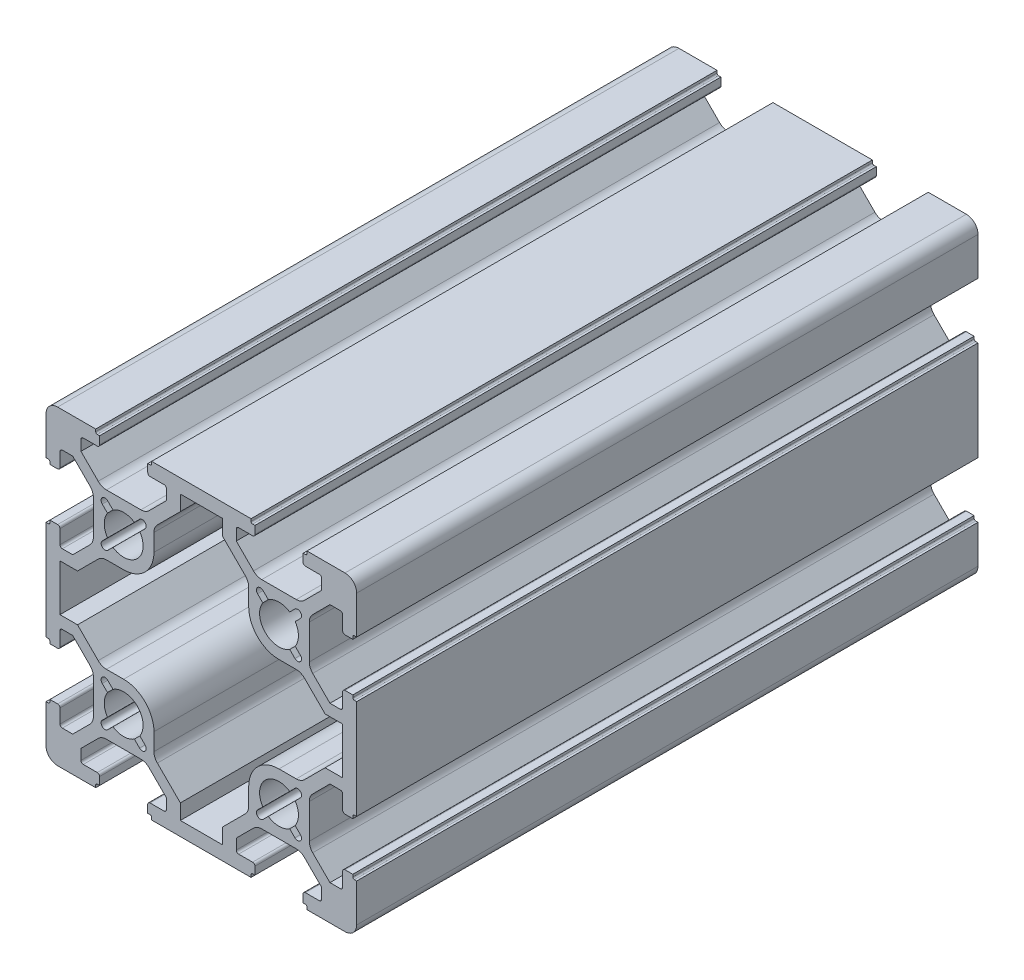
SolidWorks part; units mm, degrees
ref_plane "前视基准面" through (0, 0, 0) normal (0, 0, 1) x (1, 0, 0)
ref_plane "上视基准面" through (0, 0, 0) normal (0, 1, 0) x (1, 0, 0)
ref_plane "右视基准面" through (0, 0, 0) normal (1, 0, 0) x (0, 0, -1)
sketch "草图1" plane through (0, 0, 0) normal (0, 0, 1) x (1, 0, 0)
  line L0 (579.2639, 196.5387) -> (579.2639, 198.7573)
  line L1 (579.7033, 199.818) -> (582.6639, 202.7787)
  line L2 (583.8639, 206.5387) -> (578.9639, 206.5387)
  line L3 (578.9639, 206.5387) -> (578.9639, 206.2387)
  line L4 (578.7639, 206.0387) -> (578.4639, 206.0387)
  line L5 (578.4639, 206.0387) -> (578.4639, 205.0387)
  line L6 (578.7639, 204.7387) -> (580.5639, 204.7387)
  line L7 (580.8639, 204.4387) -> (580.8639, 203.0987)
  line L8 (580.8639, 203.0987) -> (578.6433, 200.878)
  line L9 (577.5826, 200.4387) -> (573.1452, 200.4387)
  line L10 (572.0846, 200.878) -> (569.8639, 203.0987)
  line L11 (569.8639, 203.0987) -> (569.8639, 204.4387)
  line L12 (570.1639, 204.7387) -> (571.9639, 204.7387)
  line L13 (572.2639, 205.0387) -> (572.2639, 206.0387)
  line L14 (572.2639, 206.0387) -> (571.9639, 206.0387)
  line L15 (571.7639, 206.2387) -> (571.7639, 206.5387)
  line L16 (571.7639, 206.5387) -> (566.8639, 206.5387)
  line L17 (565.3639, 205.0387) -> (565.3639, 200.1387)
  line L18 (565.3639, 200.1387) -> (565.6639, 200.1387)
  line L19 (565.8639, 199.9387) -> (565.8639, 199.6387)
  line L20 (565.8639, 199.6387) -> (566.8639, 199.6387)
  line L21 (567.1639, 199.9387) -> (567.1639, 201.7387)
  line L22 (567.4639, 202.0387) -> (568.8039, 202.0387)
  line L23 (568.8039, 202.0387) -> (571.0246, 199.818)
  line L24 (571.4639, 198.7573) -> (571.4639, 194.32)
  line L25 (571.0246, 193.2593) -> (568.8039, 191.0387)
  line L26 (568.8039, 191.0387) -> (567.4639, 191.0387)
  line L27 (567.1639, 191.3387) -> (567.1639, 193.1387)
  line L28 (566.8639, 193.4387) -> (565.8639, 193.4387)
  line L29 (565.8639, 193.4387) -> (565.8639, 193.1387)
  line L30 (565.6639, 192.9387) -> (565.3639, 192.9387)
  line L31 (565.3639, 192.9387) -> (565.3639, 180.1387)
  line L32 (569.8639, 189.9787) -> (572.0846, 192.1993)
  line L33 (573.1452, 192.6387) -> (575.3639, 192.6387)
  line L34 (588.0639, 202.7787) -> (591.0246, 199.818)
  line L35 (591.4639, 198.7573) -> (591.4639, 196.5387)
  line L36 (583.8639, 206.5387) -> (586.8639, 206.5387)
  line L37 (580.3215, 204.7387) -> (580.5639, 204.7387)
  line L38 (582.6639, 204.7387) -> (588.0639, 204.7387)
  line L39 (588.0639, 204.7387) -> (588.0639, 202.7787)
  line L40 (582.6639, 204.7387) -> (582.6639, 202.7787)
  line L41 (599.7033, 199.818) -> (601.9239, 202.0387)
  line L42 (601.9239, 202.0387) -> (603.2639, 202.0387)
  line L43 (603.5639, 201.7387) -> (603.5639, 199.9387)
  line L44 (603.8639, 199.6387) -> (604.8639, 199.6387)
  line L45 (604.8639, 199.6387) -> (604.8639, 199.9387)
  line L46 (605.0639, 200.1387) -> (605.3639, 200.1387)
  line L47 (605.3639, 200.1387) -> (605.3639, 205.0387)
  line L48 (603.8639, 206.5387) -> (598.9639, 206.5387)
  line L49 (598.9639, 206.5387) -> (598.9639, 206.2387)
  line L50 (598.7639, 206.0387) -> (598.4639, 206.0387)
  line L51 (598.4639, 206.0387) -> (598.4639, 205.0387)
  line L52 (598.7639, 204.7387) -> (600.5639, 204.7387)
  line L53 (600.8639, 204.4387) -> (600.8639, 203.0987)
  line L54 (600.8639, 203.0987) -> (598.6433, 200.878)
  line L55 (597.5826, 200.4387) -> (593.1452, 200.4387)
  line L56 (592.0846, 200.878) -> (589.8639, 203.0987)
  line L57 (589.8639, 203.0987) -> (589.8639, 204.4387)
  line L58 (590.1639, 204.7387) -> (591.9639, 204.7387)
  line L59 (592.2639, 205.0387) -> (592.2639, 206.0387)
  line L60 (592.2639, 206.0387) -> (591.9639, 206.0387)
  line L61 (591.7639, 206.2387) -> (591.7639, 206.5387)
  line L62 (591.7639, 206.5387) -> (586.8639, 206.5387)
  line L63 (586.8639, 206.5387) -> (583.8639, 206.5387)
  line L64 (583.8639, 206.5387) -> (578.9639, 206.5387)
  line L65 (578.9639, 206.5387) -> (578.9639, 206.2387)
  line L66 (578.7639, 206.0387) -> (578.4639, 206.0387)
  line L67 (578.4639, 206.0387) -> (578.4639, 205.0387)
  line L68 (578.7639, 204.7387) -> (580.5639, 204.7387)
  line L69 (580.8639, 204.4387) -> (580.8639, 203.0987)
  line L70 (580.8639, 203.0987) -> (578.6433, 200.878)
  line L71 (577.5826, 200.4387) -> (573.1452, 200.4387)
  line L72 (572.0846, 200.878) -> (569.8639, 203.0987)
  line L73 (569.8639, 203.0987) -> (569.8639, 204.4387)
  line L74 (570.1639, 204.7387) -> (571.9639, 204.7387)
  line L75 (572.2639, 205.0387) -> (572.2639, 206.0387)
  line L76 (572.2639, 206.0387) -> (571.9639, 206.0387)
  line L77 (571.7639, 206.2387) -> (571.7639, 206.5387)
  line L78 (571.7639, 206.5387) -> (566.8639, 206.5387)
  line L79 (565.3639, 205.0387) -> (565.3639, 200.1387)
  line L80 (565.3639, 200.1387) -> (565.6639, 200.1387)
  line L81 (565.8639, 199.9387) -> (565.8639, 199.6387)
  line L82 (565.8639, 199.6387) -> (566.8639, 199.6387)
  line L83 (567.1639, 199.9387) -> (567.1639, 201.7387)
  line L84 (567.4639, 202.0387) -> (568.8039, 202.0387)
  line L85 (568.8039, 202.0387) -> (571.0246, 199.818)
  line L86 (571.4639, 198.7573) -> (571.4639, 194.32)
  line L87 (571.0246, 193.2593) -> (568.8039, 191.0387)
  line L88 (568.8039, 191.0387) -> (567.4639, 191.0387)
  line L89 (569.4239, 189.5387) -> (567.1639, 189.5387)
  line L90 (567.1639, 191.3387) -> (567.1639, 193.1387)
  line L91 (566.8639, 193.4387) -> (565.8639, 193.4387)
  line L92 (565.8639, 193.4387) -> (565.8639, 193.1387)
  line L93 (565.6639, 192.9387) -> (565.3639, 192.9387)
  line L94 (565.3639, 192.9387) -> (565.3639, 180.1387)
  line L95 (567.1639, 189.5387) -> (567.1639, 183.5387)
  line L96 (569.4239, 189.5387) -> (572.0846, 192.1993)
  line L97 (573.1452, 192.6387) -> (575.3639, 192.6387)
  line L98 (595.3639, 192.6387) -> (597.5826, 192.6387)
  line L99 (598.6433, 192.1993) -> (601.3039, 189.5387)
  line L100 (605.3639, 192.9387) -> (605.0639, 192.9387)
  line L101 (604.8639, 193.1387) -> (604.8639, 193.4387)
  line L102 (604.8639, 193.4387) -> (603.8639, 193.4387)
  line L103 (603.5639, 193.1387) -> (603.5639, 191.3387)
  line L104 (603.2639, 191.0387) -> (601.9239, 191.0387)
  line L105 (601.9239, 191.0387) -> (599.7033, 193.2593)
  line L106 (599.2639, 194.32) -> (599.2639, 198.7573)
  line L107 (579.2639, 176.5387) -> (579.2639, 174.32)
  line L108 (579.7033, 173.2593) -> (582.6639, 170.2987)
  line L109 (583.8639, 166.5387) -> (578.9639, 166.5387)
  line L110 (578.9639, 166.5387) -> (578.9639, 166.8387)
  line L111 (578.7639, 167.0387) -> (578.4639, 167.0387)
  line L112 (578.4639, 167.0387) -> (578.4639, 168.0387)
  line L113 (578.7639, 168.3387) -> (580.5639, 168.3387)
  line L114 (580.8639, 168.6387) -> (580.8639, 169.9787)
  line L115 (580.8639, 169.9787) -> (578.6433, 172.1993)
  line L116 (577.5826, 172.6387) -> (573.1452, 172.6387)
  line L117 (572.0846, 172.1993) -> (569.8639, 169.9787)
  line L118 (569.8639, 169.9787) -> (569.8639, 168.6387)
  line L119 (570.1639, 168.3387) -> (571.9639, 168.3387)
  line L120 (572.2639, 168.0387) -> (572.2639, 167.0387)
  line L121 (572.2639, 167.0387) -> (571.9639, 167.0387)
  line L122 (571.7639, 166.8387) -> (571.7639, 166.5387)
  line L123 (571.7639, 166.5387) -> (566.8639, 166.5387)
  line L124 (565.3639, 168.0387) -> (565.3639, 172.9387)
  line L125 (565.3639, 172.9387) -> (565.6639, 172.9387)
  line L126 (565.8639, 173.1387) -> (565.8639, 173.4387)
  line L127 (565.8639, 173.4387) -> (566.8639, 173.4387)
  line L128 (567.1639, 173.1387) -> (567.1639, 171.3387)
  line L129 (567.4639, 171.0387) -> (568.8039, 171.0387)
  line L130 (568.8039, 171.0387) -> (571.0246, 173.2593)
  line L131 (571.4639, 174.32) -> (571.4639, 178.7573)
  line L132 (571.0246, 179.818) -> (568.8039, 182.0387)
  line L133 (568.8039, 182.0387) -> (567.4639, 182.0387)
  line L134 (567.1639, 181.7387) -> (567.1639, 179.9387)
  line L135 (566.8639, 179.6387) -> (565.8639, 179.6387)
  line L136 (565.8639, 179.6387) -> (565.8639, 179.9387)
  line L137 (565.6639, 180.1387) -> (565.3639, 180.1387)
  line L138 (569.8639, 183.0987) -> (572.0846, 180.878)
  line L139 (573.1452, 180.4387) -> (575.3639, 180.4387)
  line L140 (588.0639, 170.2987) -> (591.0246, 173.2593)
  line L141 (591.4639, 174.32) -> (591.4639, 176.5387)
  line L142 (583.8639, 166.5387) -> (586.8639, 166.5387)
  line L143 (580.3215, 168.3387) -> (580.5639, 168.3387)
  line L144 (582.6639, 168.3387) -> (588.0639, 168.3387)
  line L145 (588.0639, 168.3387) -> (588.0639, 170.2987)
  line L146 (582.6639, 168.3387) -> (582.6639, 170.2987)
  line L147 (599.7033, 173.2593) -> (601.9239, 171.0387)
  line L148 (601.9239, 171.0387) -> (603.2639, 171.0387)
  line L149 (603.5639, 171.3387) -> (603.5639, 173.1387)
  line L150 (603.8639, 173.4387) -> (604.8639, 173.4387)
  line L151 (604.8639, 173.4387) -> (604.8639, 173.1387)
  line L152 (605.0639, 172.9387) -> (605.3639, 172.9387)
  line L153 (605.3639, 172.9387) -> (605.3639, 168.0387)
  line L154 (603.8639, 166.5387) -> (598.9639, 166.5387)
  line L155 (598.9639, 166.5387) -> (598.9639, 166.8387)
  line L156 (598.7639, 167.0387) -> (598.4639, 167.0387)
  line L157 (598.4639, 167.0387) -> (598.4639, 168.0387)
  line L158 (598.7639, 168.3387) -> (600.5639, 168.3387)
  line L159 (600.8639, 168.6387) -> (600.8639, 169.9787)
  line L160 (600.8639, 169.9787) -> (598.6433, 172.1993)
  line L161 (597.5826, 172.6387) -> (593.1452, 172.6387)
  line L162 (592.0846, 172.1993) -> (589.8639, 169.9787)
  line L163 (589.8639, 169.9787) -> (589.8639, 168.6387)
  line L164 (590.1639, 168.3387) -> (591.9639, 168.3387)
  line L165 (592.2639, 168.0387) -> (592.2639, 167.0387)
  line L166 (592.2639, 167.0387) -> (591.9639, 167.0387)
  line L167 (591.7639, 166.8387) -> (591.7639, 166.5387)
  line L168 (591.7639, 166.5387) -> (586.8639, 166.5387)
  line L169 (586.8639, 166.5387) -> (583.8639, 166.5387)
  line L170 (583.8639, 166.5387) -> (578.9639, 166.5387)
  line L171 (578.9639, 166.5387) -> (578.9639, 166.8387)
  line L172 (578.7639, 167.0387) -> (578.4639, 167.0387)
  line L173 (578.4639, 167.0387) -> (578.4639, 168.0387)
  line L174 (578.7639, 168.3387) -> (580.5639, 168.3387)
  line L175 (580.8639, 168.6387) -> (580.8639, 169.9787)
  line L176 (580.8639, 169.9787) -> (578.6433, 172.1993)
  line L177 (577.5826, 172.6387) -> (573.1452, 172.6387)
  line L178 (572.0846, 172.1993) -> (569.8639, 169.9787)
  line L179 (569.8639, 169.9787) -> (569.8639, 168.6387)
  line L180 (570.1639, 168.3387) -> (571.9639, 168.3387)
  line L181 (572.2639, 168.0387) -> (572.2639, 167.0387)
  line L182 (572.2639, 167.0387) -> (571.9639, 167.0387)
  line L183 (571.7639, 166.8387) -> (571.7639, 166.5387)
  line L184 (571.7639, 166.5387) -> (566.8639, 166.5387)
  line L185 (565.3639, 168.0387) -> (565.3639, 172.9387)
  line L186 (565.3639, 172.9387) -> (565.6639, 172.9387)
  line L187 (565.8639, 173.1387) -> (565.8639, 173.4387)
  line L188 (565.8639, 173.4387) -> (566.8639, 173.4387)
  line L189 (567.1639, 173.1387) -> (567.1639, 171.3387)
  line L190 (567.4639, 171.0387) -> (568.8039, 171.0387)
  line L191 (568.8039, 171.0387) -> (571.0246, 173.2593)
  line L192 (571.4639, 174.32) -> (571.4639, 178.7573)
  line L193 (571.0246, 179.818) -> (568.8039, 182.0387)
  line L194 (568.8039, 182.0387) -> (567.4639, 182.0387)
  line L195 (569.4239, 183.5387) -> (567.1639, 183.5387)
  line L196 (567.1639, 181.7387) -> (567.1639, 179.9387)
  line L197 (566.8639, 179.6387) -> (565.8639, 179.6387)
  line L198 (565.8639, 179.6387) -> (565.8639, 179.9387)
  line L199 (565.6639, 180.1387) -> (565.3639, 180.1387)
  line L200 (569.4239, 183.5387) -> (572.0846, 180.878)
  line L201 (573.1452, 180.4387) -> (575.3639, 180.4387)
  line L202 (595.3639, 180.4387) -> (597.5826, 180.4387)
  line L203 (598.6433, 180.878) -> (601.3039, 183.5387)
  line L204 (605.3639, 180.1387) -> (605.0639, 180.1387)
  line L205 (604.8639, 179.9387) -> (604.8639, 179.6387)
  line L206 (604.8639, 179.6387) -> (603.8639, 179.6387)
  line L207 (603.5639, 179.9387) -> (603.5639, 181.7387)
  line L208 (603.2639, 182.0387) -> (601.9239, 182.0387)
  line L209 (601.9239, 182.0387) -> (599.7033, 179.818)
  line L210 (599.2639, 178.7573) -> (599.2639, 174.32)
  line L211 (605.3639, 192.9387) -> (605.3639, 180.1387)
  line L212 (601.3039, 189.5387) -> (603.5639, 189.5387)
  line L213 (603.5639, 189.5387) -> (603.5639, 183.5387)
  line L214 (601.3039, 183.5387) -> (603.5639, 183.5387)
  line L215 (577.4145, 199.2964) -> (576.7424, 198.6243)
  line L216 (578.1216, 198.5893) -> (577.4495, 197.9172)
  line L217 (573.3133, 199.2964) -> (573.9854, 198.6243)
  line L218 (572.6062, 198.5893) -> (573.2783, 197.9172)
  line L219 (573.3133, 193.7809) -> (573.9854, 194.4531)
  line L220 (572.6062, 194.4881) -> (573.2783, 195.1602)
  line L221 (593.3133, 199.2964) -> (593.9854, 198.6243)
  line L222 (592.6062, 198.5893) -> (593.2783, 197.9172)
  line L223 (597.4145, 199.2964) -> (596.7424, 198.6243)
  line L224 (598.1216, 198.5893) -> (597.4495, 197.9172)
  line L225 (597.4145, 193.7809) -> (596.7424, 194.4531)
  line L226 (598.1216, 194.4881) -> (597.4495, 195.1602)
  line L227 (577.4145, 173.7809) -> (576.7424, 174.4531)
  line L228 (578.1216, 174.4881) -> (577.4495, 175.1602)
  line L229 (573.3133, 173.7809) -> (573.9854, 174.4531)
  line L230 (572.6062, 174.4881) -> (573.2783, 175.1602)
  line L231 (573.3133, 179.2964) -> (573.9854, 178.6243)
  line L232 (572.6062, 178.5893) -> (573.2783, 177.9172)
  line L233 (593.3133, 173.7809) -> (593.9854, 174.4531)
  line L234 (592.6062, 174.4881) -> (593.2783, 175.1602)
  line L235 (597.4145, 173.7809) -> (596.7424, 174.4531)
  line L236 (597.4145, 179.2964) -> (596.7424, 178.6243)
  line L237 (598.1216, 178.5893) -> (597.4495, 177.9172)
  line L238 (598.1216, 174.4881) -> (597.4495, 175.1602)
  arc A0 (573.9854, 194.4531) -> (577.4495, 197.9172) centre (575.3639, 196.5387) ccw
  arc A1 (573.2783, 197.9172) -> (573.2783, 195.1602) centre (575.3639, 196.5387) ccw
  arc A2 (576.7424, 198.6243) -> (573.9854, 198.6243) centre (575.3639, 196.5387) ccw
  arc A3 (579.7033, 199.818) -> (579.2639, 198.7573) centre (580.7639, 198.7573) ccw
  arc A4 (578.7639, 206.0387) -> (578.9639, 206.2387) centre (578.7639, 206.2387) ccw
  arc A5 (578.4639, 205.0387) -> (578.7639, 204.7387) centre (578.7639, 205.0387) ccw
  arc A6 (580.8639, 204.4387) -> (580.5639, 204.7387) centre (580.5639, 204.4387) ccw
  arc A7 (577.5826, 200.4387) -> (578.6433, 200.878) centre (577.5826, 201.9387) ccw
  arc A8 (572.0846, 200.878) -> (573.1452, 200.4387) centre (573.1452, 201.9387) ccw
  arc A9 (570.1639, 204.7387) -> (569.8639, 204.4387) centre (570.1639, 204.4387) ccw
  arc A10 (571.9639, 204.7387) -> (572.2639, 205.0387) centre (571.9639, 205.0387) ccw
  arc A11 (571.7639, 206.2387) -> (571.9639, 206.0387) centre (571.9639, 206.2387) ccw
  arc A12 (566.8639, 206.5387) -> (565.3639, 205.0387) centre (566.8639, 205.0387) ccw
  arc A13 (565.8639, 199.9387) -> (565.6639, 200.1387) centre (565.6639, 199.9387) ccw
  arc A14 (566.8639, 199.6387) -> (567.1639, 199.9387) centre (566.8639, 199.9387) ccw
  arc A15 (567.4639, 202.0387) -> (567.1639, 201.7387) centre (567.4639, 201.7387) ccw
  arc A16 (571.4639, 198.7573) -> (571.0246, 199.818) centre (569.9639, 198.7573) ccw
  arc A17 (571.0246, 193.2593) -> (571.4639, 194.32) centre (569.9639, 194.32) ccw
  arc A18 (567.1639, 191.3387) -> (567.4639, 191.0387) centre (567.4639, 191.3387) ccw
  arc A19 (567.1639, 193.1387) -> (566.8639, 193.4387) centre (566.8639, 193.1387) ccw
  arc A20 (565.6639, 192.9387) -> (565.8639, 193.1387) centre (565.6639, 193.1387) ccw
  arc A21 (573.1452, 192.6387) -> (572.0846, 192.1993) centre (573.1452, 191.1387) ccw
  arc A22 (591.4639, 198.7573) -> (591.0246, 199.818) centre (589.9639, 198.7573) ccw
  arc A23 (596.7424, 198.6243) -> (593.9854, 198.6243) centre (595.3639, 196.5387) ccw
  arc A24 (597.4495, 195.1602) -> (597.4495, 197.9172) centre (595.3639, 196.5387) ccw
  arc A25 (593.2783, 197.9172) -> (596.7424, 194.4531) centre (595.3639, 196.5387) ccw
  arc A26 (596.7424, 198.6243) -> (593.9854, 198.6243) centre (595.3639, 196.5387) ccw
  arc A27 (597.4495, 195.1602) -> (597.4495, 197.9172) centre (595.3639, 196.5387) ccw
  arc A28 (593.2783, 197.9172) -> (596.7424, 194.4531) centre (595.3639, 196.5387) ccw
  arc A29 (573.9854, 194.4531) -> (577.4495, 197.9172) centre (575.3639, 196.5387) ccw
  arc A30 (573.2783, 197.9172) -> (573.2783, 195.1602) centre (575.3639, 196.5387) ccw
  arc A31 (576.7424, 198.6243) -> (573.9854, 198.6243) centre (575.3639, 196.5387) ccw
  arc A32 (603.5639, 201.7387) -> (603.2639, 202.0387) centre (603.2639, 201.7387) ccw
  arc A33 (603.5639, 199.9387) -> (603.8639, 199.6387) centre (603.8639, 199.9387) ccw
  arc A34 (605.0639, 200.1387) -> (604.8639, 199.9387) centre (605.0639, 199.9387) ccw
  arc A35 (605.3639, 205.0387) -> (603.8639, 206.5387) centre (603.8639, 205.0387) ccw
  arc A36 (598.7639, 206.0387) -> (598.9639, 206.2387) centre (598.7639, 206.2387) ccw
  arc A37 (598.4639, 205.0387) -> (598.7639, 204.7387) centre (598.7639, 205.0387) ccw
  arc A38 (600.8639, 204.4387) -> (600.5639, 204.7387) centre (600.5639, 204.4387) ccw
  arc A39 (597.5826, 200.4387) -> (598.6433, 200.878) centre (597.5826, 201.9387) ccw
  arc A40 (592.0846, 200.878) -> (593.1452, 200.4387) centre (593.1452, 201.9387) ccw
  arc A41 (590.1639, 204.7387) -> (589.8639, 204.4387) centre (590.1639, 204.4387) ccw
  arc A42 (591.9639, 204.7387) -> (592.2639, 205.0387) centre (591.9639, 205.0387) ccw
  arc A43 (591.7639, 206.2387) -> (591.9639, 206.0387) centre (591.9639, 206.2387) ccw
  arc A44 (578.7639, 206.0387) -> (578.9639, 206.2387) centre (578.7639, 206.2387) ccw
  arc A45 (578.4639, 205.0387) -> (578.7639, 204.7387) centre (578.7639, 205.0387) ccw
  arc A46 (580.8639, 204.4387) -> (580.5639, 204.7387) centre (580.5639, 204.4387) ccw
  arc A47 (577.5826, 200.4387) -> (578.6433, 200.878) centre (577.5826, 201.9387) ccw
  arc A48 (572.0846, 200.878) -> (573.1452, 200.4387) centre (573.1452, 201.9387) ccw
  arc A49 (570.1639, 204.7387) -> (569.8639, 204.4387) centre (570.1639, 204.4387) ccw
  arc A50 (571.9639, 204.7387) -> (572.2639, 205.0387) centre (571.9639, 205.0387) ccw
  arc A51 (571.7639, 206.2387) -> (571.9639, 206.0387) centre (571.9639, 206.2387) ccw
  arc A52 (566.8639, 206.5387) -> (565.3639, 205.0387) centre (566.8639, 205.0387) ccw
  arc A53 (565.8639, 199.9387) -> (565.6639, 200.1387) centre (565.6639, 199.9387) ccw
  arc A54 (566.8639, 199.6387) -> (567.1639, 199.9387) centre (566.8639, 199.9387) ccw
  arc A55 (567.4639, 202.0387) -> (567.1639, 201.7387) centre (567.4639, 201.7387) ccw
  arc A56 (571.4639, 198.7573) -> (571.0246, 199.818) centre (569.9639, 198.7573) ccw
  arc A57 (571.0246, 193.2593) -> (571.4639, 194.32) centre (569.9639, 194.32) ccw
  arc A58 (567.1639, 191.3387) -> (567.4639, 191.0387) centre (567.4639, 191.3387) ccw
  arc A59 (567.1639, 193.1387) -> (566.8639, 193.4387) centre (566.8639, 193.1387) ccw
  arc A60 (565.6639, 192.9387) -> (565.8639, 193.1387) centre (565.6639, 193.1387) ccw
  arc A61 (573.1452, 192.6387) -> (572.0846, 192.1993) centre (573.1452, 191.1387) ccw
  arc A62 (598.6433, 192.1993) -> (597.5826, 192.6387) centre (597.5826, 191.1387) ccw
  arc A63 (604.8639, 193.1387) -> (605.0639, 192.9387) centre (605.0639, 193.1387) ccw
  arc A64 (603.8639, 193.4387) -> (603.5639, 193.1387) centre (603.8639, 193.1387) ccw
  arc A65 (603.2639, 191.0387) -> (603.5639, 191.3387) centre (603.2639, 191.3387) ccw
  arc A66 (599.2639, 194.32) -> (599.7033, 193.2593) centre (600.7639, 194.32) ccw
  arc A67 (599.7033, 199.818) -> (599.2639, 198.7573) centre (600.7639, 198.7573) ccw
  arc A68 (573.9854, 174.4531) -> (576.7424, 174.4531) centre (575.3639, 176.5387) ccw
  arc A69 (577.4495, 175.1602) -> (573.9854, 178.6243) centre (575.3639, 176.5387) ccw
  arc A70 (573.2783, 177.9172) -> (573.2783, 175.1602) centre (575.3639, 176.5387) ccw
  arc A71 (579.2639, 174.32) -> (579.7033, 173.2593) centre (580.7639, 174.32) ccw
  arc A72 (578.9639, 166.8387) -> (578.7639, 167.0387) centre (578.7639, 166.8387) ccw
  arc A73 (578.7639, 168.3387) -> (578.4639, 168.0387) centre (578.7639, 168.0387) ccw
  arc A74 (580.5639, 168.3387) -> (580.8639, 168.6387) centre (580.5639, 168.6387) ccw
  arc A75 (578.6433, 172.1993) -> (577.5826, 172.6387) centre (577.5826, 171.1387) ccw
  arc A76 (573.1452, 172.6387) -> (572.0846, 172.1993) centre (573.1452, 171.1387) ccw
  arc A77 (569.8639, 168.6387) -> (570.1639, 168.3387) centre (570.1639, 168.6387) ccw
  arc A78 (572.2639, 168.0387) -> (571.9639, 168.3387) centre (571.9639, 168.0387) ccw
  arc A79 (571.9639, 167.0387) -> (571.7639, 166.8387) centre (571.9639, 166.8387) ccw
  arc A80 (565.3639, 168.0387) -> (566.8639, 166.5387) centre (566.8639, 168.0387) ccw
  arc A81 (565.6639, 172.9387) -> (565.8639, 173.1387) centre (565.6639, 173.1387) ccw
  arc A82 (567.1639, 173.1387) -> (566.8639, 173.4387) centre (566.8639, 173.1387) ccw
  arc A83 (567.1639, 171.3387) -> (567.4639, 171.0387) centre (567.4639, 171.3387) ccw
  arc A84 (571.0246, 173.2593) -> (571.4639, 174.32) centre (569.9639, 174.32) ccw
  arc A85 (571.4639, 178.7573) -> (571.0246, 179.818) centre (569.9639, 178.7573) ccw
  arc A86 (567.4639, 182.0387) -> (567.1639, 181.7387) centre (567.4639, 181.7387) ccw
  arc A87 (566.8639, 179.6387) -> (567.1639, 179.9387) centre (566.8639, 179.9387) ccw
  arc A88 (565.8639, 179.9387) -> (565.6639, 180.1387) centre (565.6639, 179.9387) ccw
  arc A89 (572.0846, 180.878) -> (573.1452, 180.4387) centre (573.1452, 181.9387) ccw
  arc A90 (591.0246, 173.2593) -> (591.4639, 174.32) centre (589.9639, 174.32) ccw
  arc A91 (596.7424, 178.6243) -> (593.2783, 175.1602) centre (595.3639, 176.5387) ccw
  arc A92 (593.9854, 174.4531) -> (596.7424, 174.4531) centre (595.3639, 176.5387) ccw
  arc A93 (597.4495, 175.1602) -> (597.4495, 177.9172) centre (595.3639, 176.5387) ccw
  arc A94 (596.7424, 178.6243) -> (593.2783, 175.1602) centre (595.3639, 176.5387) ccw
  arc A95 (593.9854, 174.4531) -> (596.7424, 174.4531) centre (595.3639, 176.5387) ccw
  arc A96 (597.4495, 175.1602) -> (597.4495, 177.9172) centre (595.3639, 176.5387) ccw
  arc A97 (573.2783, 177.9172) -> (573.2783, 175.1602) centre (575.3639, 176.5387) ccw
  arc A98 (573.9854, 174.4531) -> (576.7424, 174.4531) centre (575.3639, 176.5387) ccw
  arc A99 (577.4495, 175.1602) -> (573.9854, 178.6243) centre (575.3639, 176.5387) ccw
  arc A100 (603.2639, 171.0387) -> (603.5639, 171.3387) centre (603.2639, 171.3387) ccw
  arc A101 (603.8639, 173.4387) -> (603.5639, 173.1387) centre (603.8639, 173.1387) ccw
  arc A102 (604.8639, 173.1387) -> (605.0639, 172.9387) centre (605.0639, 173.1387) ccw
  arc A103 (603.8639, 166.5387) -> (605.3639, 168.0387) centre (603.8639, 168.0387) ccw
  arc A104 (598.9639, 166.8387) -> (598.7639, 167.0387) centre (598.7639, 166.8387) ccw
  arc A105 (598.7639, 168.3387) -> (598.4639, 168.0387) centre (598.7639, 168.0387) ccw
  arc A106 (600.5639, 168.3387) -> (600.8639, 168.6387) centre (600.5639, 168.6387) ccw
  arc A107 (598.6433, 172.1993) -> (597.5826, 172.6387) centre (597.5826, 171.1387) ccw
  arc A108 (593.1452, 172.6387) -> (592.0846, 172.1993) centre (593.1452, 171.1387) ccw
  arc A109 (589.8639, 168.6387) -> (590.1639, 168.3387) centre (590.1639, 168.6387) ccw
  arc A110 (592.2639, 168.0387) -> (591.9639, 168.3387) centre (591.9639, 168.0387) ccw
  arc A111 (591.9639, 167.0387) -> (591.7639, 166.8387) centre (591.9639, 166.8387) ccw
  arc A112 (578.9639, 166.8387) -> (578.7639, 167.0387) centre (578.7639, 166.8387) ccw
  arc A113 (578.7639, 168.3387) -> (578.4639, 168.0387) centre (578.7639, 168.0387) ccw
  arc A114 (580.5639, 168.3387) -> (580.8639, 168.6387) centre (580.5639, 168.6387) ccw
  arc A115 (578.6433, 172.1993) -> (577.5826, 172.6387) centre (577.5826, 171.1387) ccw
  arc A116 (573.1452, 172.6387) -> (572.0846, 172.1993) centre (573.1452, 171.1387) ccw
  arc A117 (569.8639, 168.6387) -> (570.1639, 168.3387) centre (570.1639, 168.6387) ccw
  arc A118 (572.2639, 168.0387) -> (571.9639, 168.3387) centre (571.9639, 168.0387) ccw
  arc A119 (571.9639, 167.0387) -> (571.7639, 166.8387) centre (571.9639, 166.8387) ccw
  arc A120 (565.3639, 168.0387) -> (566.8639, 166.5387) centre (566.8639, 168.0387) ccw
  arc A121 (565.6639, 172.9387) -> (565.8639, 173.1387) centre (565.6639, 173.1387) ccw
  arc A122 (567.1639, 173.1387) -> (566.8639, 173.4387) centre (566.8639, 173.1387) ccw
  arc A123 (567.1639, 171.3387) -> (567.4639, 171.0387) centre (567.4639, 171.3387) ccw
  arc A124 (571.0246, 173.2593) -> (571.4639, 174.32) centre (569.9639, 174.32) ccw
  arc A125 (571.4639, 178.7573) -> (571.0246, 179.818) centre (569.9639, 178.7573) ccw
  arc A126 (567.4639, 182.0387) -> (567.1639, 181.7387) centre (567.4639, 181.7387) ccw
  arc A127 (566.8639, 179.6387) -> (567.1639, 179.9387) centre (566.8639, 179.9387) ccw
  arc A128 (565.8639, 179.9387) -> (565.6639, 180.1387) centre (565.6639, 179.9387) ccw
  arc A129 (572.0846, 180.878) -> (573.1452, 180.4387) centre (573.1452, 181.9387) ccw
  arc A130 (597.5826, 180.4387) -> (598.6433, 180.878) centre (597.5826, 181.9387) ccw
  arc A131 (605.0639, 180.1387) -> (604.8639, 179.9387) centre (605.0639, 179.9387) ccw
  arc A132 (603.5639, 179.9387) -> (603.8639, 179.6387) centre (603.8639, 179.9387) ccw
  arc A133 (603.5639, 181.7387) -> (603.2639, 182.0387) centre (603.2639, 181.7387) ccw
  arc A134 (599.7033, 179.818) -> (599.2639, 178.7573) centre (600.7639, 178.7573) ccw
  arc A135 (599.2639, 174.32) -> (599.7033, 173.2593) centre (600.7639, 174.32) ccw
  arc A136 (575.3639, 192.6387) -> (579.2639, 196.5387) centre (575.3639, 196.5387) ccw
  arc A137 (591.4639, 196.5387) -> (595.3639, 192.6387) centre (595.3639, 196.5387) ccw
  arc A138 (595.3639, 180.4387) -> (591.4639, 176.5387) centre (595.3639, 176.5387) ccw
  arc A139 (579.2639, 176.5387) -> (575.3639, 180.4387) centre (575.3639, 176.5387) ccw
  arc A140 (578.1216, 198.5893) -> (577.4145, 199.2964) centre (577.7681, 198.9428) ccw
  arc A141 (573.3133, 199.2964) -> (572.6062, 198.5893) centre (572.9598, 198.9428) ccw
  arc A142 (572.6062, 194.4881) -> (573.3133, 193.7809) centre (572.9598, 194.1345) ccw
  arc A143 (593.3133, 199.2964) -> (592.6062, 198.5893) centre (592.9598, 198.9428) ccw
  arc A144 (598.1216, 198.5893) -> (597.4145, 199.2964) centre (597.7681, 198.9428) ccw
  arc A145 (597.4145, 193.7809) -> (598.1216, 194.4881) centre (597.7681, 194.1345) ccw
  arc A146 (573.2783, 177.9172) -> (573.2783, 175.1602) centre (575.3639, 176.5387) ccw
  arc A147 (573.2783, 177.9172) -> (573.2783, 175.1602) centre (575.3639, 176.5387) ccw
  arc A148 (577.4145, 173.7809) -> (578.1216, 174.4881) centre (577.7681, 174.1345) ccw
  arc A149 (572.6062, 174.4881) -> (573.3133, 173.7809) centre (572.9598, 174.1345) ccw
  arc A150 (573.3133, 179.2964) -> (572.6062, 178.5893) centre (572.9598, 178.9428) ccw
  arc A151 (592.6062, 174.4881) -> (593.3133, 173.7809) centre (592.9598, 174.1345) ccw
  arc A152 (597.4145, 173.7809) -> (598.1216, 174.4881) centre (597.7681, 174.1345) ccw
  arc A153 (598.1216, 178.5893) -> (597.4145, 179.2964) centre (597.7681, 178.9428) ccw
extrude "凸台-拉伸1" add sketch "草图1" along normal blind 80 contours A135 L210 A134 L209 L208 A133 L207 A132 L206 L205 A131 L204 L211 L100 A63 L101 L102 A64 L103 A65 L104 L105 A66 L106 A67 L41 L42 A32 L43 A33 L44 L45 A34 L46 L47 A35 L48 L49 A36 L50 L51 A37 L52 A38 L53 L54 A39 L55 A40 L56 L57
